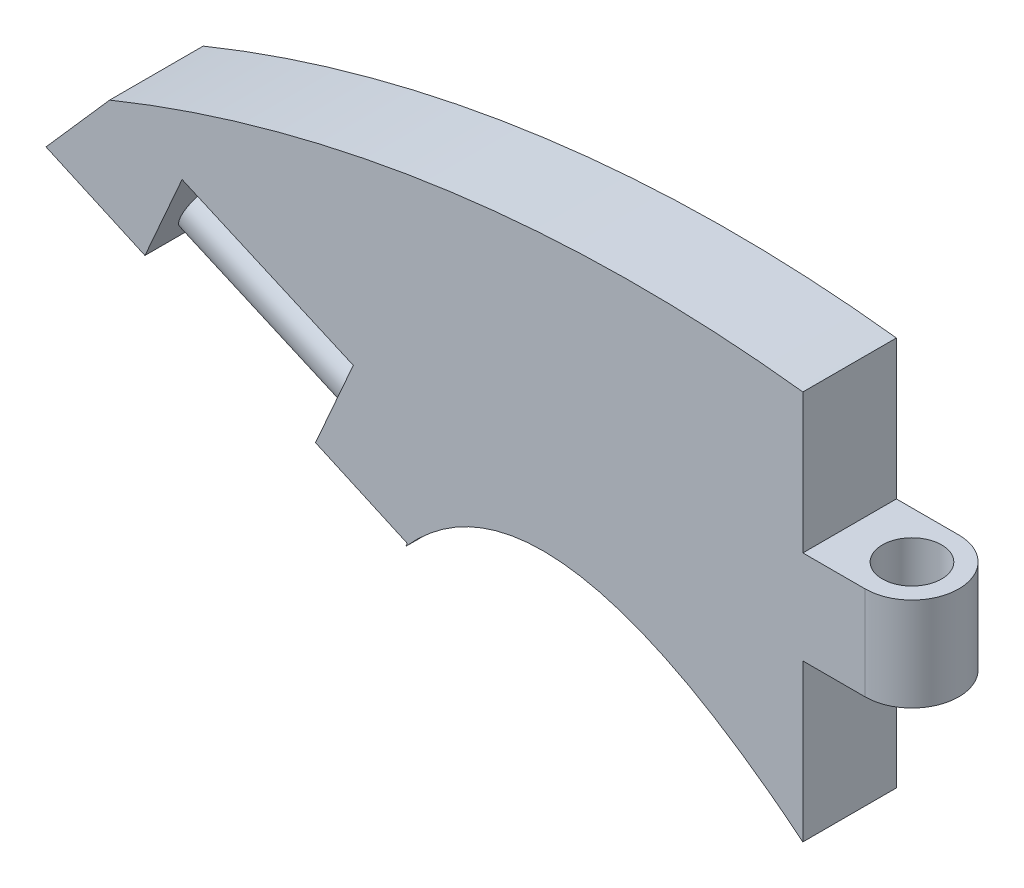
SolidWorks part; units mm, degrees
ref_plane "Alzado" through (0, 0, 0) normal (0, 0, 1) x (1, 0, 0)
ref_plane "Planta" through (0, 0, 0) normal (0, 1, 0) x (1, 0, 0)
ref_plane "Vista lateral" through (0, 0, 0) normal (1, 0, 0) x (0, 0, -1)
sketch "Croquis1" plane through (0, 0, 0) normal (0, 0, 1) x (1, 0, 0)
  line L3 (0, 24.9429) -> (0, 0) construction
  line L4 (-92.7757, 24.9429) -> (-60, 50) construction
  line L5 (-26.569, 2.2644) -> (-54.0293, 14.3447)
  line L6 (0, 24.9429) -> (0, -0.0571)
  line L7 (-92.7757, 24.9429) -> (92.7757, 24.9429) construction
  arc A2 (0, 24.9429) -> (-54.0293, 14.3447) centre (-10.6006, -64.0343) ccw
  spline S0 degree 2 poles (-26.569, 2.2644) (-17.7474, 14.3657) (0, -0.0571) knots 0 0 0 1 1 1
  dimension "D3" = 30
  dimension "D2" = 25
extrude "Saliente-Extruir1" add sketch "Croquis1" along normal blind 6
sketch "Croquis2" plane through (0, 0, 6) normal (0, 0, 1) x (1, 0, 0)
  line L0 (-43.0452, 9.5126) -> (-39.8238, 16.8353)
  line L1 (-54.0293, 14.3447) -> (-26.569, 2.2644) construction
  line L2 (-39.8238, 16.8353) -> (-28.8397, 12.0032)
  line L3 (-28.8397, 12.0032) -> (-32.0611, 4.6805)
  line L4 (-54.0293, 14.3447) -> (-54.0293, 29.0043) construction
  line L5 (-43.0452, 9.5126) -> (-32.0611, 4.6805)
  dimension "D1" = 8
  dimension "D2" = 12
  dimension "D3" = 8
  dimension "D4" = 6
extrude "Cortar-Extruir2" cut sketch "Croquis2" against normal blind 10
sketch "Croquis3" plane through (-28.5876, 12.5762, 0) normal (-0.9153, 0.4027, 0) x (0, 0, 1)
  line L0 (0, -8.626) -> (6, -8.626) construction
  line L1 (0, -8.626) -> (0, -0.626) construction
  circle A0 centre (3, -4.626) radius 1.5
  point P4 (0, 0)
  point P6 (2.2334, -4.5658)
  dimension "D1" = 3
  dimension "D2" = 4
  dimension "D3" = 3
extrude "Saliente-Extruir2" add sketch "Croquis3" along normal up to next
sketch "Croquis4" plane through (0, 0, 0) normal (0, 1, 0) x (1, 0, 0)
  line L0 (0, -6) -> (0, 0) construction
  line L1 (0, 0) -> (4, 0)
  line L2 (0, 0) -> (0, -6)
  line L3 (0, -6) -> (4, -6)
  arc A0 (4, 0) -> (4, -6) centre (4, -3) cw
  dimension "D1" = 6
  dimension "D2" = 4
extrude "Saliente-Extruir3" add sketch "Croquis4" along normal blind 6 from offset 10
sketch "Croquis5" plane through (0, 16, 0) normal (0, 1, 0) x (1, 0, 0)
  circle A0 centre (4, -3) radius 1.9
  dimension "D1" = 3.8
extrude "Cortar-Extruir3" cut sketch "Croquis5" against normal blind 6
sketch "Croquis6" plane through (0, 0, 6) normal (0, 0, 1) x (1, 0, 0)
  line L0 (-54.2173, 14.2402) -> (-26.345, 1.6869)
  line L1 (-26.345, 1.6869) -> (-25.3747, 3.8414)
  line L2 (-25.3747, 3.8414) -> (-53.247, 16.3947)
  line L3 (-53.247, 16.3947) -> (-54.2173, 14.2402)
  arc A0 (0, 24.9429) -> (-54.0293, 14.3447) centre (-10.6006, -64.0343) ccw construction
extrude "Cortar-Extruir4" cut sketch "Croquis6" against normal blind 10
sketch "Croquis7" plane through (0, 0, 6) normal (0, 0, 1) x (1, 0, 0)
  line L0 (-42.2053, 11.4217) -> (-51.5891, 15.648) construction
  line L1 (-44.4697, 18.9248) -> (-48.5538, 14.2809)
  arc A0 (-48.5538, 14.2809) -> (-44.4697, 18.9248) centre (-44.1898, 14.5608) cw
  arc A1 (0, 24.9429) -> (-51.5891, 15.648) centre (-10.6006, -64.0343) ccw construction
  dimension "D1" = 4.6439
extrude "Cortar-Extruir8" cut sketch "Croquis7" against normal blind 10
